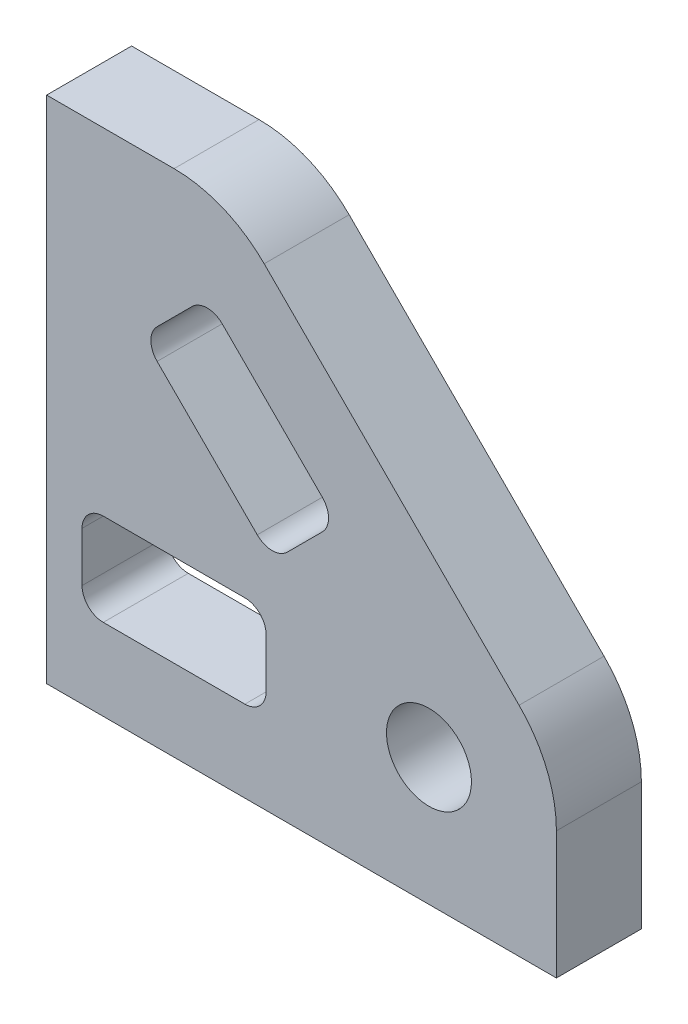
SolidWorks part; units mm, degrees
ref_plane "Alzado" through (0, 0, 0) normal (0, 0, 1) x (1, 0, 0)
ref_plane "Planta" through (0, 0, 0) normal (0, 1, 0) x (1, 0, 0)
ref_plane "Vista lateral" through (0, 0, 0) normal (1, 0, 0) x (0, 0, -1)
sketch "Model" plane through (0, 0, 0) normal (0, 0, 1) x (1, 0, 0)
  line L0 (180.8421, 175.824) -> (162.8421, 175.824)
  line L1 (162.8421, 193.824) -> (162.8421, 175.824)
  line L2 (164.8421, 181.949) -> (169.8421, 181.949)
  line L3 (170.5921, 181.199) -> (170.5921, 179.449)
  line L4 (169.8421, 178.699) -> (164.8421, 178.699)
  line L5 (164.0921, 179.449) -> (164.0921, 181.199)
  line L6 (180.8421, 180.324) -> (180.8421, 175.824)
  line L7 (167.3421, 193.824) -> (162.8421, 193.824)
  line L8 (179.5241, 183.5059) -> (170.5241, 192.5059)
  line L9 (169.0413, 189.9287) -> (172.5769, 186.3931)
  line L10 (172.5769, 185.3325) -> (171.3394, 184.095)
  line L11 (170.2788, 184.095) -> (166.7433, 187.6306)
  line L12 (166.7433, 188.6912) -> (167.9807, 189.9287)
  arc A0 (180.8421, 180.324) -> (179.5241, 183.5059) centre (176.3421, 180.324) ccw
  arc A1 (170.5241, 192.5059) -> (167.3421, 193.824) centre (167.3421, 189.324) ccw
  arc A2 (170.5921, 181.199) -> (169.8421, 181.949) centre (169.8421, 181.199) ccw
  arc A3 (169.8421, 178.699) -> (170.5921, 179.449) centre (169.8421, 179.449) ccw
  arc A4 (164.0921, 179.449) -> (164.8421, 178.699) centre (164.8421, 179.449) ccw
  arc A5 (164.8421, 181.949) -> (164.0921, 181.199) centre (164.8421, 181.199) ccw
  arc A6 (172.5769, 185.3325) -> (172.5769, 186.3931) centre (172.0466, 185.8628) ccw
  arc A7 (170.2788, 184.095) -> (171.3394, 184.095) centre (170.8091, 184.6254) ccw
  arc A8 (166.7433, 188.6912) -> (166.7433, 187.6306) centre (167.2736, 188.1609) ccw
  arc A9 (169.0413, 189.9287) -> (167.9807, 189.9287) centre (168.511, 189.3983) ccw
  circle A10 centre (176.3421, 180.324) radius 1.5
extrude "Saliente-Extruir1" add sketch "Model" along normal blind 3
